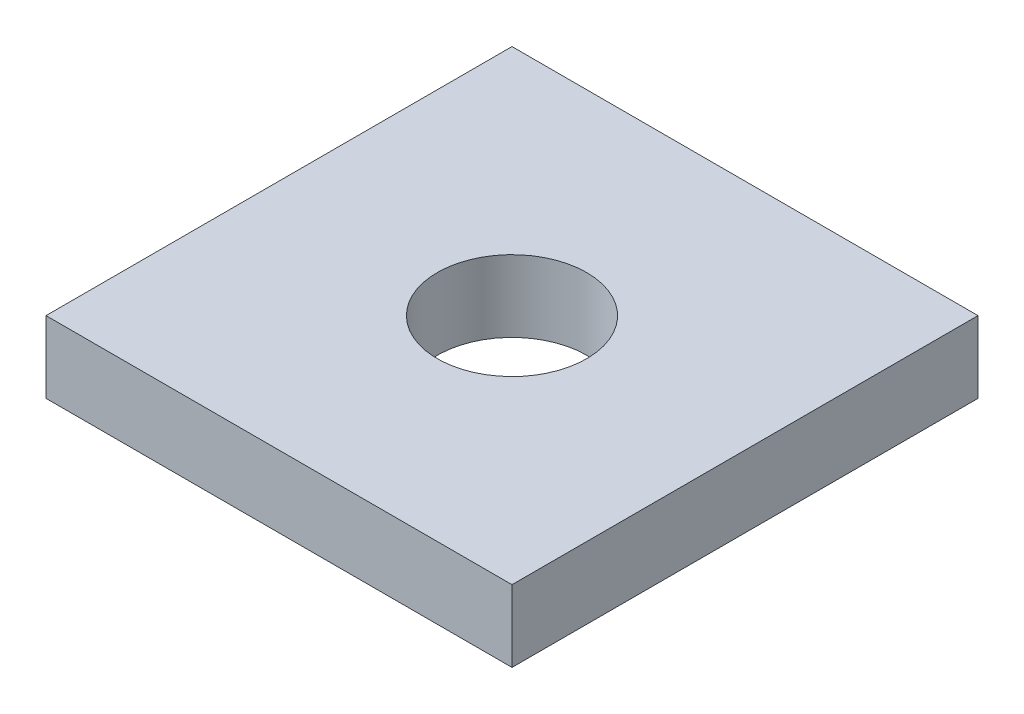
SolidWorks part; units mm, degrees
ref_plane "Front Plane" through (0, 0, 0) normal (0, 0, 1) x (1, 0, 0)
ref_plane "Top Plane" through (0, 0, 0) normal (0, 1, 0) x (1, 0, 0)
ref_plane "Right Plane" through (0, 0, 0) normal (1, 0, 0) x (0, 0, -1)
sketch "Sketch2" plane through (0, 0, 0) normal (0, 1, 0) x (1, 0, 0)
  line L1 (0, 0) -> (-39, 0)
  line L2 (0, 0) -> (0, -39)
  line L3 (0, -39) -> (-39, -39)
  line L4 (-39, 0) -> (-39, -39)
  dimension "D1" = 39
  dimension "D2" = 39
extrude "Boss-Extrude2" add sketch "Sketch2" against normal blind 6
sketch "Sketch4" plane through (0, -6, 0) normal (0, -1, 0) x (1, 0, 0)
  circle A0 centre (-19.5, 19.5) radius 6.25
  dimension "D1" = 12.5
extrude "Cut-Extrude2" cut sketch "Sketch4" against normal blind 6
